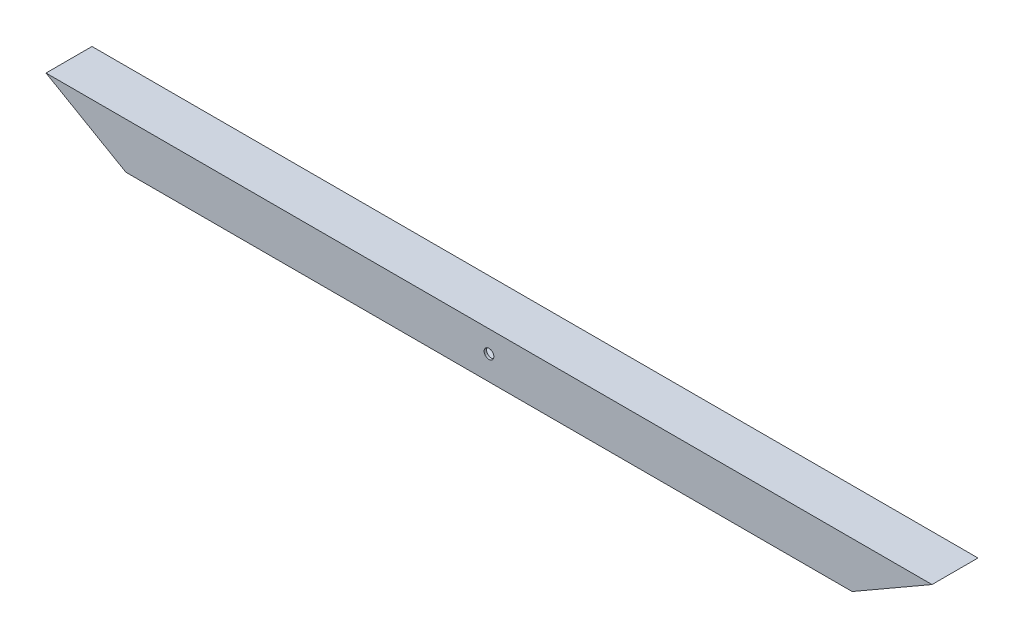
SolidWorks part; units mm, degrees
ref_plane "Front Plane" through (0, 0, 0) normal (0, 0, 1) x (1, 0, 0)
ref_plane "Top Plane" through (0, 0, 0) normal (0, 1, 0) x (1, 0, 0)
ref_plane "Right Plane" through (0, 0, 0) normal (1, 0, 0) x (0, 0, -1)
sketch "Sketch1" plane through (0, 0, 0) normal (0, 1, 0) x (1, 0, 0)
  line L1 (-336.9356, 19) -> (29.0644, 19)
  line L2 (-336.9356, 19) -> (-336.9356, 0)
  line L3 (-336.9356, 0) -> (29.0644, 0)
  line L4 (29.0644, 19) -> (29.0644, 0)
  line L5 (-336.9356, 19) -> (29.0644, 0) construction
  line L6 (-336.9356, 0) -> (29.0644, 19) construction
  point P0 (-153.9356, 9.5)
  dimension "D1" = 19
  dimension "D2" = 366
extrude "Boss-Extrude2" add sketch "Sketch1" along normal blind 19
sketch "Sketch9" plane through (29.0644, 0, 0) normal (1, 0, 0) x (0, 0, -1)
  line L0 (0, 19) -> (19, 19) construction
  line L1 (1, 18) -> (18, 18)
  line L2 (1, 18) -> (1, 1)
  line L3 (1, 1) -> (18, 1)
  line L4 (18, 18) -> (18, 1)
  line L5 (0, 19) -> (0, 0) construction
  dimension "D1" = 17
  dimension "D2" = 17
  dimension "D3" = 1
  dimension "D4" = 1
extrude "Cut-Extrude4" cut sketch "Sketch9" against normal through all
sketch "Sketch11" plane through (0, 0, -19) normal (0, 0, -1) x (-1, 0, 0)
  line L0 (3.9356, 0) -> (3.9356, 19)
  line L1 (-29.0644, 0) -> (336.9356, 0) construction
  line L2 (-29.0644, 19) -> (336.9356, 19) construction
  line L3 (303.9356, 0) -> (303.9356, 19)
  line L4 (-29.0644, 19) -> (-29.0644, 0) construction
  line L5 (336.9356, 19) -> (336.9356, 0) construction
  line L6 (303.9356, 0) -> (336.9356, 19)
  line L7 (336.9356, 19) -> (336.9356, 0)
  line L8 (336.9356, 0) -> (303.9356, 0)
  line L9 (3.9356, 0) -> (-29.0644, 19)
  line L10 (-29.0644, 19) -> (-29.0644, 0)
  line L11 (-29.0644, 0) -> (3.9356, 0)
  dimension "D1" = 33
  dimension "D2" = 33
extrude "Cut-Extrude6" cut sketch "Sketch11" against normal through all contours L4 L9 L7 | L6 L4 L5
sketch "Sketch12" plane through (0, 0, 0) normal (0, 0, 1) x (1, 0, 0)
  line L0 (-303.9356, 0) -> (-3.9356, 0) construction
  line L1 (-303.9356, 0) -> (-303.9356, 52.621) construction
  line L2 (-303.9356, 0) -> (-336.9356, 19) construction
  circle A0 centre (-153.9356, 10) radius 2
  dimension "D1" = 4
  dimension "D2" = 10
  dimension "D3" = 150
extrude "Cut-Extrude7" cut sketch "Sketch12" against normal through all
